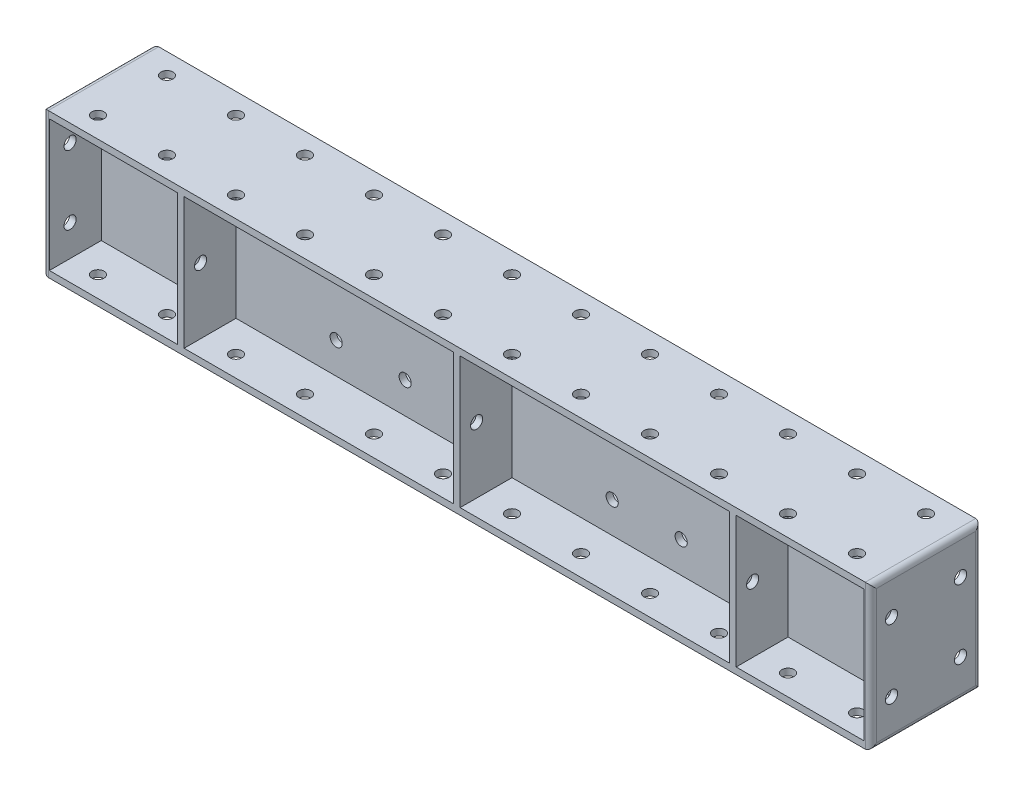
SolidWorks part; units mm, degrees
ref_plane "前视基准面" through (0, 0, 0) normal (0, 0, 1) x (1, 0, 0)
ref_plane "上视基准面" through (0, 0, 0) normal (0, 1, 0) x (1, 0, 0)
ref_plane "右视基准面" through (0, 0, 0) normal (1, 0, 0) x (0, 0, -1)
sketch "草图1" plane through (0, 0, 0) normal (0, 0, 1) x (1, 0, 0)
  line L1 (0, 0) -> (1500, 0)
  line L2 (0, 0) -> (0, 262)
  line L3 (0, 262) -> (1500, 262)
  line L4 (1500, 0) -> (1500, 262)
  dimension "D1" = 1500
  dimension "D2" = 262
extrude "拉伸1" add sketch "草图1" along normal blind 200
sketch "草图5" plane through (0, 0, 200) normal (0, 0, 1) x (1, 0, 0)
  line L0 (1500, 262) -> (0, 262) construction
  line L1 (12, 250) -> (244, 250)
  line L2 (12, 250) -> (12, 12)
  line L3 (12, 12) -> (244, 12)
  line L4 (244, 250) -> (244, 12)
  line L5 (0, 0) -> (1500, 0) construction
  line L6 (0, 262) -> (0, 0) construction
  line L8 (256, 250) -> (744, 250)
  line L9 (256, 250) -> (256, 12)
  line L10 (256, 12) -> (744, 12)
  line L11 (744, 250) -> (744, 12)
  line L12 (756, 250) -> (1244, 250)
  line L13 (756, 250) -> (756, 12)
  line L14 (756, 12) -> (1244, 12)
  line L15 (1244, 250) -> (1244, 12)
  line L32 (1256, 250) -> (1488, 250)
  line L33 (1256, 250) -> (1256, 12)
  line L34 (1256, 12) -> (1488, 12)
  line L35 (1488, 250) -> (1488, 12)
  dimension "D1" = 12
  dimension "D2" = 12
  dimension "D3" = 12
  dimension "D4" = 232
  dimension "D5" = 12
  dimension "D6" = 488
  dimension "D7" = 488
  dimension "D8" = 12
  dimension "D9" = 12
  dimension "D17" = 232
extrude "拉伸10" cut sketch "草图5" against normal through all
sketch "草图7" plane through (0, 0, 0) normal (0, -1, 0) x (1, 0, 0)
  line L0 (0, 100) -> (3607.9066, 100) construction
  line L1 (0, 200) -> (0, 0) construction
  line L2 (1500, 200) -> (1500, 0) construction
  line L3 (0, 106) -> (1500, 106)
  line L4 (0, 106) -> (0, 94)
  line L5 (0, 94) -> (1500, 94)
  line L6 (1500, 106) -> (1500, 94)
  dimension "D1" = 6
  dimension "D2" = 6
extrude "拉伸13" add sketch "草图7" against normal blind 260
sketch "草图8" plane through (0, 0, 0) normal (0, -1, 0) x (1, 0, 0)
  line L0 (0, 0) -> (1500, 0) construction
  line L1 (0, 200) -> (0, 0) construction
  circle A0 centre (62.5, 37.5) radius 11
  dimension "D1" = 37.5
  dimension "D3" = 22
  dimension "D2" = 62.5
extrude "拉伸14" cut sketch "草图8" against normal through all
pattern_linear "阵列(线性)3" count 12 spacing 125 along (1, 0, 0) count 2 spacing 125 along (0, 0, 1) of "拉伸14"
sketch "草图10" plane through (0, 0, 0) normal (-1, 0, 0) x (0, 0, 1)
  line L0 (200, 0) -> (0, 0) construction
  line L1 (0, 262) -> (0, 0) construction
  circle A0 centre (37.5, 68.5) radius 11
  dimension "D1" = 68.5
  dimension "D3" = 22
  dimension "D2" = 37.5
extrude "拉伸16" cut sketch "草图10" against normal blind 20
pattern_linear "阵列(线性)5" count 2 spacing 125 along (0, 0, 1) count 2 spacing 125 along (0, 1, 0) of "拉伸16"
sketch "草图11" plane through (1500, 0, 0) normal (1, 0, 0) x (0, 0, -1)
  line L0 (-200, 0) -> (0, 0) construction
  line L1 (-200, 0) -> (-200, 262) construction
  circle A0 centre (-162.5, 68.5) radius 11
  dimension "D1" = 68.5
  dimension "D3" = 22
  dimension "D2" = 37.5
extrude "拉伸17" cut sketch "草图11" against normal blind 20
pattern_linear "阵列(线性)6" count 2 spacing 125 along (0, 0, -1) count 2 spacing 125 along (0, 1, 0) of "拉伸17"
sketch "草图12" plane through (1256, 0, 0) normal (1, 0, 0) x (0, 0, -1)
  line L0 (-200, 250) -> (-200, 12) construction
  line L1 (-106, 12) -> (-200, 12) construction
  circle A0 centre (-170.1213, 131) radius 11
  dimension "D1" = 29.8787
  dimension "D3" = 22
  dimension "D2" = 119
extrude "拉伸18" cut sketch "草图12" against normal blind 1050
pattern_linear "阵列(线性)8" count 2 spacing 140.2427 along (0, 0, -1) of "拉伸18"
fillet "圆角1" radius 10 4 edges at (0, 0, 100) (0, 131, 0) (0, 131, 200) (0, 262, 100)
fillet "圆角2" radius 10 4 edges at (1500, 262, 100) (1500, 131, 0) (1500, 0, 100) (1500, 131, 200)
sketch "草图13" plane through (0, 0, 106) normal (0, 0, 1) x (1, 0, 0)
  line L0 (256, 12) -> (744, 12) construction
  line L2 (256, 250) -> (256, 12) construction
  circle A0 centre (437.5, 68.5) radius 11
  dimension "D1" = 56.5
  dimension "D3" = 22
  dimension "D2" = 181.5
extrude "拉伸19" cut sketch "草图13" against normal through all
pattern_linear "阵列(线性)9" count 2 spacing 125 along (1, 0, 0) count 2 spacing 125 along (0, 1, 0) of "拉伸19"
pattern_linear "阵列(线性)10" count 2 spacing 500 along (1, 0, 0) of "拉伸19", "阵列(线性)9"
